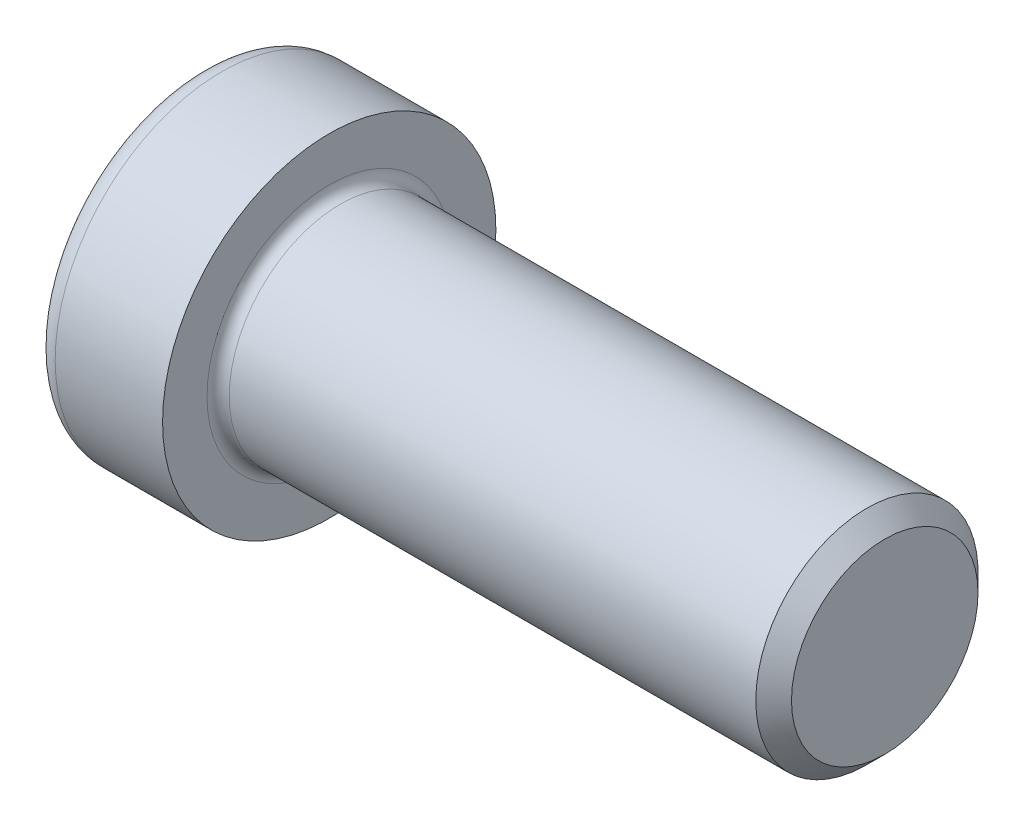
SolidWorks part; units mm, degrees
revolve "Base-Revolve" add sketch "BodySke"
sketch "BodySke" plane through (0, 0, 0) normal (0, 0, 1) x (1, 0, 0)
  line L0 (0, 0) -> (0, 9)
  line L1 (0, 9) -> (7, 9)
  line L2 (7, 9) -> (7, 6)
  line L3 (7, 6) -> (36.036, 6)
  line L4 (37, 5.036) -> (37, 0)
  line L5 (37, 0) -> (0, 0)
  line L6 (-31.75, 0) -> (127, 0) construction
  line L8 (37, 5.036) -> (36.036, 6)
  line L10 (37, -5.036) -> (36.036, -6) construction
  line L11 (8.75, 4.525) -> (8.75, -1.825) construction
  line L12 (12.25, 4.525) -> (12.25, -1.825) construction
  line L13 (-23, 4.525) -> (-23, -1.825) construction
  dimension "Head_ht" = 7
  dimension "Length" = 30
  dimension "Body_ch_ang" = 45
  dimension "Diameter" = 12
  dimension "Minor_dia" = 10.072
  dimension "Advance" = 1.75
  dimension "Thread_nom" = 24.75
  dimension "Thread_length" = 60
  dimension "Head_dia" = 18
cosmetic thread "ThreadCosmetic"
fillet "Fillet1" radius 0.6 1 edges at (7, 0, 6)
fillet "Fillet2" radius 1.2 1 edges at (0, 0, 9)
material "AISI 316 Нержавеющая сталь, лист (SS)"
ref_plane "Plane1" through (0, 0, 0) normal (0, 0, 1) x (1, 0, 0)
ref_plane "Plane2" through (0, 0, 0) normal (0, 1, 0) x (1, 0, 0)
ref_plane "Plane3" through (0, 0, 0) normal (1, 0, 0) x (0, 0, -1)
other "Configuration Table"
sketch "Sketch2" plane through (0, 0, 0) normal (0, 0, 1) x (1, 0, 0)
  line L0 (0, 4) -> (5, 4)
  line L1 (5, 4) -> (7.3094, 0)
  line L2 (-31.75, 0) -> (127, 0) construction
  line L3 (7.3094, 0) -> (0, 0)
  line L4 (0, 0) -> (0, 4)
  line L6 (0, 0) -> (47.625, 0) construction
  dimension "D1" = 4
  dimension "D2" = 60
  dimension "Depth" = 5
revolve "Hex-PreBroach" cut sketch "Sketch2" angle 360 about L6
sketch "Sketch3" plane through (0, 0, 0) normal (-1, 0, 0) x (0, 0.5, 0.866)
  line L0 (2.3094, 4) -> (-2.3094, 4)
  line L1 (-2.3094, 4) -> (-4.6188, 0)
  line L2 (2.3094, 4) -> (4.6188, 0)
  line L3 (2.3094, -4) -> (4.6188, 0)
  line L4 (2.3094, -4) -> (-2.3094, -4)
  line L5 (-2.3094, -4) -> (-4.6188, 0)
  dimension "D1" = 4
  dimension "D2" = 4
  dimension "Hex_size" = 8
extrude "Hex" cut sketch "Sketch3" against normal blind 5
sketch "ThdSchSke" plane through (0, 0, 0) normal (0, 0, 1) x (1, 0, 0)
  line L0 (12.25, -5.036) -> (11.575, -6)
  line L1 (12.25, -5.036) -> (12.925, -6)
  line L2 (12.925, -6) -> (12.925, -7.5)
  line L3 (-3.175, 0) -> (5.1513, 0) construction
  line L4 (0, 7.8) -> (0, -7.8) construction
  line L5 (12.925, -7.5) -> (11.575, -7.5)
  line L6 (11.575, -7.5) -> (11.575, -6)
  dimension "Thread_minor" = 10.072
  dimension "Diameter" = 12
  dimension "Start" = 12.25
revolve "ThreadSchematic" [suppressed] cut sketch "ThdSchSke" angle 360 about L3
pattern_linear "ThdSchPat" [suppressed]
equation "\"D2@Sketch3\" = \"Hex_size@Sketch3\" / 2"
equation "\"D1@Sketch3\" = \"Hex_size@Sketch3\" / 2"
equation "\"D1@Sketch2\" = \"Hex_size@Sketch3\" / 2"
equation "\"Thread_minor@ThreadCosmetic\"  =  \"Minor_dia@BodySke\""
equation "\"Depth@Sketch2\" =  \"Key_eng@Hex\""
equation "\"Thread_length@ThreadCosmetic\" = ((sgn( (\"Length@BodySke\" - \"Advance@BodySke\" * 3.0) - \"Thread_nom@BodySke\" )-1)*( (\"Length@BodySke\" - \"Advance@BodySke\" * 3.0) - \"Thread_nom@BodySke\" ))/-2+ \"Thread_nom@BodySke\""
equation "\"Thread_minor@ThdSchSke\" = \"Minor_dia@BodySke\""
equation "\"Diameter@ThdSchSke\" = \"Diameter@BodySke\""
equation "\"Overcut@ThdSchSke\" = \"Diameter@BodySke\" * 1.25"
equation "\"Start@ThdSchSke\" = \"Head_ht@BodySke\" + \"Length@BodySke\" - \"Thread_length@ThreadCosmetic\"  '---Non-countersunk---"
equation "\"Num_threads@ThdSchPat\" = int( \"Thread_length@ThreadCosmetic\" / \"Advance@BodySke\" + 0.999 )  + 1"
equation "\"Advance@ThdSchPat\" = \"Thread_length@ThreadCosmetic\" /  (\"Num_threads@ThdSchPat\" - 1) 'relax it"
equation "\"Num_threads@ThdSchPat\" = \"Num_threads@ThdSchPat\" - sgn( \"Num_threads@ThdSchPat\" - 1) '---chamfered tips only---"
